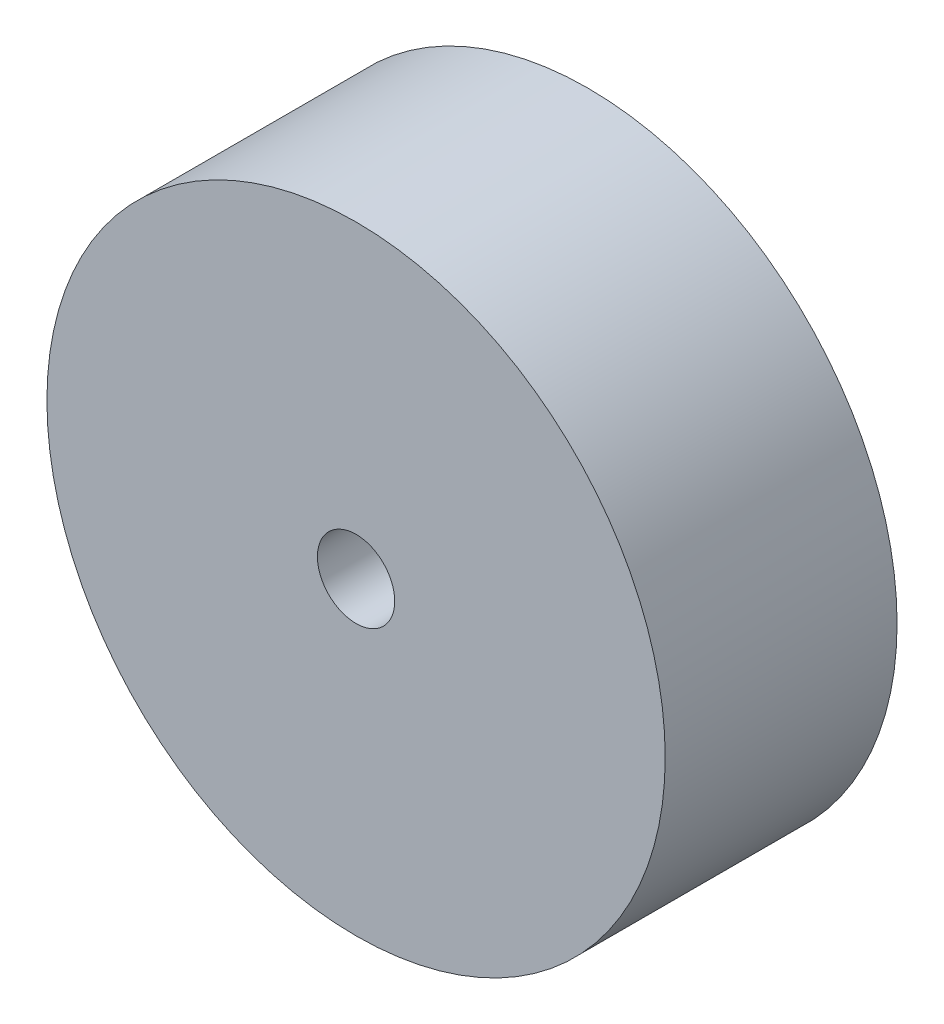
SolidWorks part; units mm, degrees
ref_plane "Front Plane" through (0, 0, 0) normal (0, 0, 1) x (1, 0, 0)
ref_plane "Top Plane" through (0, 0, 0) normal (0, 1, 0) x (1, 0, 0)
ref_plane "Right Plane" through (0, 0, 0) normal (1, 0, 0) x (0, 0, -1)
sketch "Sketch1" plane through (0, 0, 0) normal (0, 0, 1) x (1, 0, 0)
  circle A0 centre (0, 0) radius 25.4
  circle A1 centre (0, 0) radius 3.175
  dimension "D1" = 50.8
  dimension "D2" = 6.35
extrude "Boss-Extrude1" add sketch "Sketch1" along normal blind 19.05
